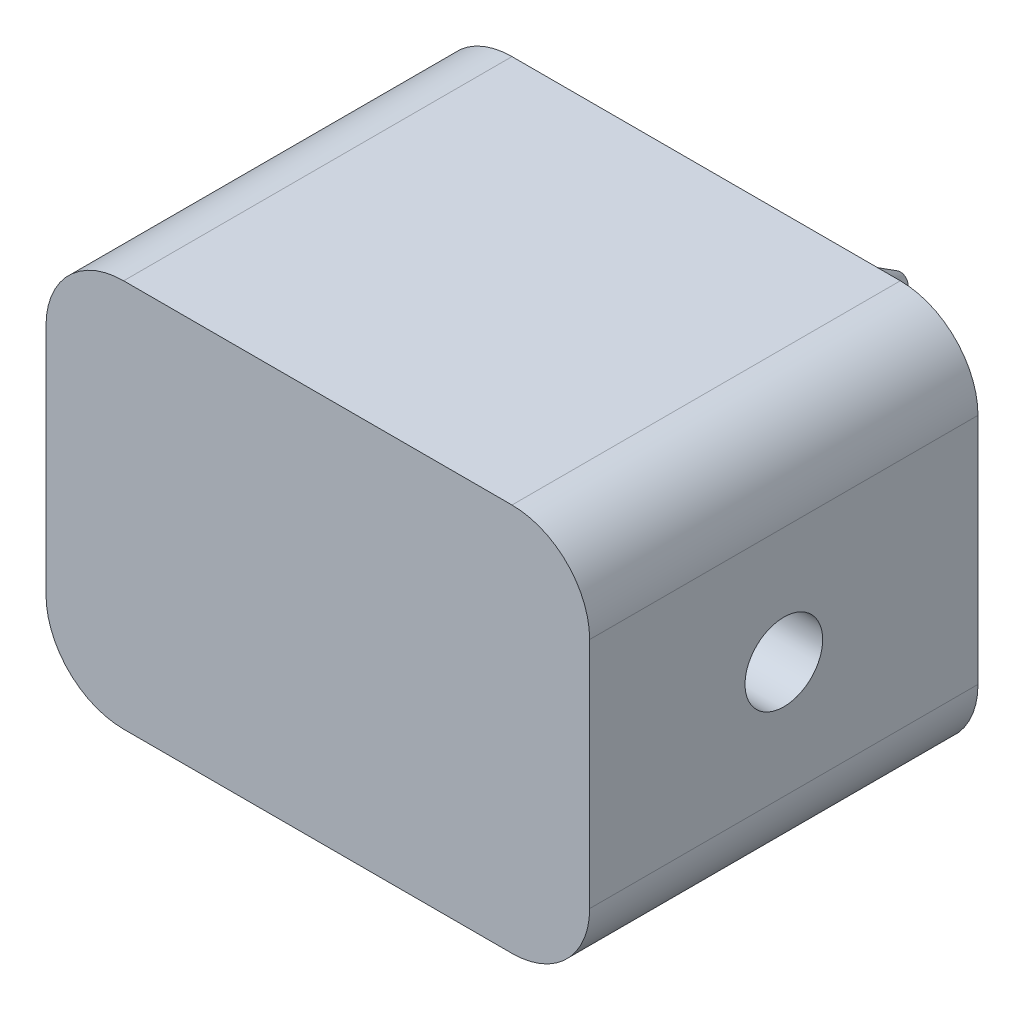
SolidWorks part; units mm, degrees
ref_plane "Front Plane" through (0, 0, 0) normal (0, 0, 1) x (1, 0, 0)
ref_plane "Top Plane" through (0, 0, 0) normal (0, 1, 0) x (1, 0, 0)
ref_plane "Right Plane" through (0, 0, 0) normal (1, 0, 0) x (0, 0, -1)
sketch "Sketch1" plane through (0, 0, 0) normal (0, 0, 1) x (1, 0, 0)
  line L1 (0, 0) -> (70, 0)
  line L2 (0, 0) -> (0, 50)
  line L3 (0, 50) -> (70, 50)
  line L4 (70, 0) -> (70, 50)
  dimension "D1" = 50
  dimension "D2" = 70
extrude "Boss-Extrude1" add sketch "Sketch1" along normal blind 50
sketch "Sketch2" plane through (70, 0, 0) normal (1, 0, 0) x (0, 0, -1)
  line L0 (-50, 50) -> (0, 50) construction
  line L1 (0, 0) -> (0, 50) construction
  circle A0 centre (-25, 25) radius 5
  dimension "D1" = 10
  dimension "D2" = 25
  dimension "D3" = 25
extrude "Cut-Extrude1" cut sketch "Sketch2" against normal through all
sketch "Sketch3" plane through (0, 0, 0) normal (0, 0, -1) x (-1, 0, 0)
  line L0 (-70, 50) -> (0, 50) construction
  line L1 (0, 50) -> (0, 0) construction
  circle A0 centre (-35, 25) radius 15
  dimension "D1" = 30
  dimension "D2" = 25
  dimension "D3" = 35
extrude "Boss-Extrude2" add sketch "Sketch3" along normal blind 10
ref_plane "Plane1" through (35, 0, 0) normal (1, 0, 0) x (0, 0, -1)
sketch "Sketch4" plane through (35, 0, 0) normal (1, 0, 0) x (0, 0, -1)
  line L0 (10, 25) -> (25, 25) construction
  line L1 (10, 10) -> (10, 40) construction
  line L2 (10, 25) -> (10, 35)
  line L3 (25, 25) -> (25, 26)
  line L4 (25, 26) -> (10, 35)
  line L5 (10, 25) -> (25, 25)
  dimension "D1" = 15
  dimension "D2" = 10
  dimension "D3" = 1
revolve "Revolve1" add sketch "Sketch4" angle 360 about L0
fillet "Fillet1" radius 3 1 edges at (20, 25, -10)
fillet "Fillet2" radius 10 4 edges at (0, 0, 25) (0, 50, 25) (70, 0, 25) (70, 50, 25)
